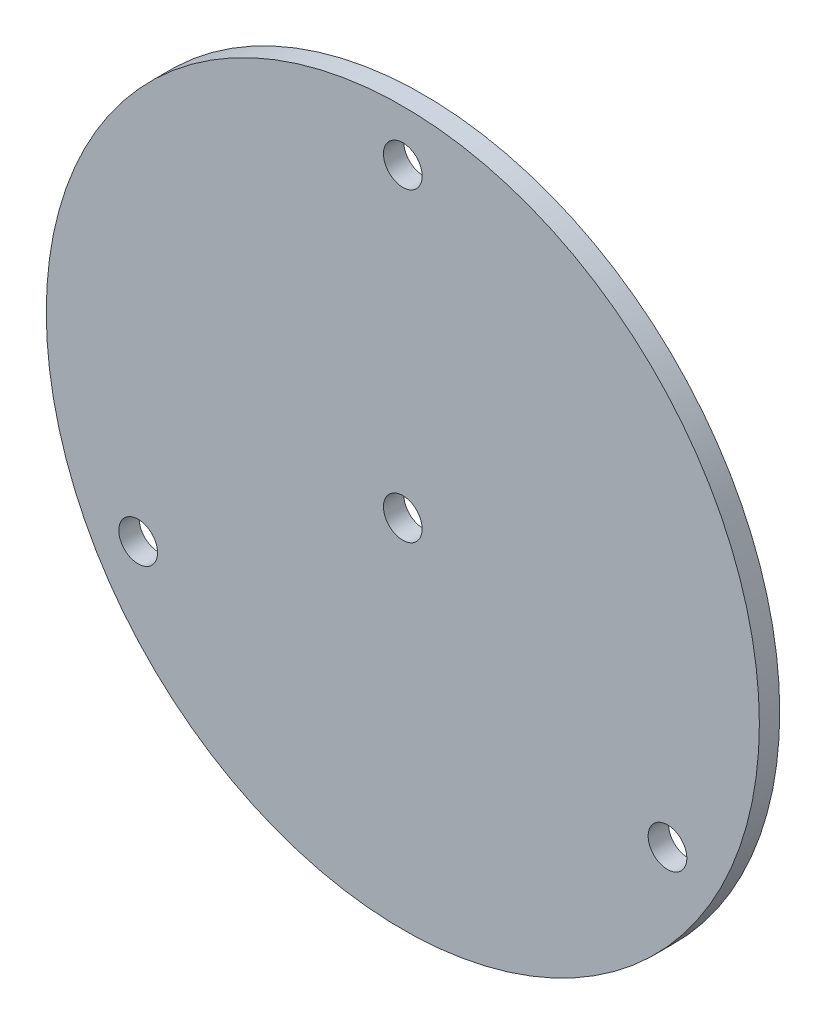
SolidWorks part; units mm, degrees
ref_plane "正面" through (0, 0, 0) normal (0, 0, 1) x (1, 0, 0)
ref_plane "平面" through (0, 0, 0) normal (0, 1, 0) x (1, 0, 0)
ref_plane "右側面" through (0, 0, 0) normal (1, 0, 0) x (0, 0, -1)
sketch "ｽｹｯﾁ1" plane through (0, 0, 0) normal (0, 0, 1) x (1, 0, 0)
  circle A0 centre (0, 0) radius 35
  dimension "D1" = 70
extrude "ﾎﾞｽ - 押し出し1" add sketch "ｽｹｯﾁ1" along normal blind 2
sketch "ｽｹｯﾁ2" plane through (0, 0, 0) normal (0, 0, 1) x (1, 0, 0)
  circle A0 centre (0, 0) radius 30 construction
  circle A1 centre (0, 30) radius 1.9
  circle A2 centre (25.9808, -15) radius 1.9
  circle A3 centre (-25.9808, -15) radius 1.9
  circle A4 centre (0, 0) radius 1.9
  point P11 (0, 0)
  dimension "D1" = 60
  dimension "D2" = 3.8
  dimension "D3" = 3
extrude "ｶｯﾄ - 押し出し1" cut sketch "ｽｹｯﾁ2" against normal through all both and the other way through all
equation "\"D1@ｽｹｯﾁ2\"=30*2"
